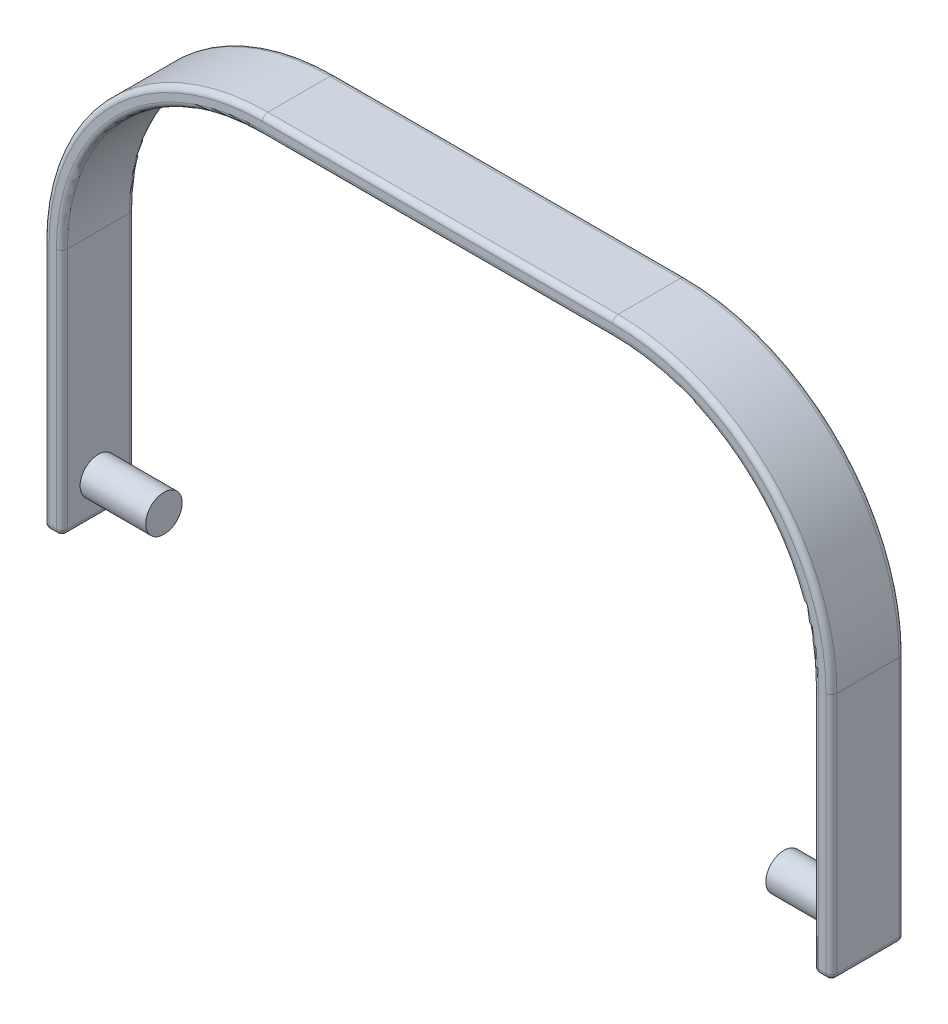
SolidWorks part; units mm, degrees
ref_plane "正面" through (0, 0, 0) normal (0, 0, 1) x (1, 0, 0)
ref_plane "平面" through (0, 0, 0) normal (0, 1, 0) x (1, 0, 0)
ref_plane "右側面" through (0, 0, 0) normal (1, 0, 0) x (0, 0, -1)
sketch "ｽｹｯﾁ2" plane through (0, 0, 0) normal (0, 0, 1) x (1, 0, 0)
  line L1 (0, 0) -> (216, 0)
  line L2 (0, 0) -> (0, 128)
  line L3 (0, 128) -> (216, 128)
  line L4 (216, 0) -> (216, 128)
extrude "ﾎﾞｽ - 押し出し1" add sketch "ｽｹｯﾁ2" along normal blind 20
fillet "ﾌｨﾚｯﾄ1" radius 60 2 edges at (216, 128, 10) (0, 128, 10)
sketch "ｽｹｯﾁ3" plane through (0, 0, 20) normal (0, 0, 1) x (1, 0, 0)
  line L0 (5, 68) -> (5, 0)
  line L1 (0, 0) -> (216, 0) construction
  line L2 (60, 123) -> (156, 123)
  line L3 (211, 68) -> (211, 0)
  arc A0 (5, 68) -> (60, 123) centre (60, 68) cw
  arc A1 (211, 68) -> (156, 123) centre (156, 68) ccw
extrude "ｶｯﾄ - 押し出し1" cut sketch "ｽｹｯﾁ3" against normal blind 20 and the other way through all flip side to cut
sketch "ｽｹｯﾁ4" plane through (5, 0, 0) normal (1, 0, 0) x (0, 0, -1)
  circle A0 centre (-10, 10) radius 5
extrude "ﾎﾞｽ - 押し出し2" add sketch "ｽｹｯﾁ4" along normal blind 18
sketch "ｽｹｯﾁ5" plane through (211, 0, 0) normal (-1, 0, 0) x (0, 0, 1)
  circle A0 centre (10, 10) radius 5
extrude "ﾎﾞｽ - 押し出し3" add sketch "ｽｹｯﾁ5" along normal blind 18
fillet "ﾌｨﾚｯﾄ2" radius 1.5 28 edges at (213.5, 0, 20) (213.5, 0, 0) (211, 0, 10) (216, 0, 10) (2.5, 0, 0) (5, 0, 10) (2.5, 0, 20) (0, 0, 10) (216, 34, 20) (108, 128, 20) (198.4264, 110.4264, 20) (0, 34, 20) (17.5736, 110.4264, 20) (216, 34, 0) (198.4264, 110.4264, 0) (108, 128, 0) (17.5736, 110.4264, 0) (0, 34, 0) (5, 34, 20) (21.1091, 106.8909, 20) (108, 123, 20) (194.8909, 106.8909, 20) (211, 34, 20) (5, 34, 0) (21.1091, 106.8909, 0) (108, 123, 0) (194.8909, 106.8909, 0) (211, 34, 0)
